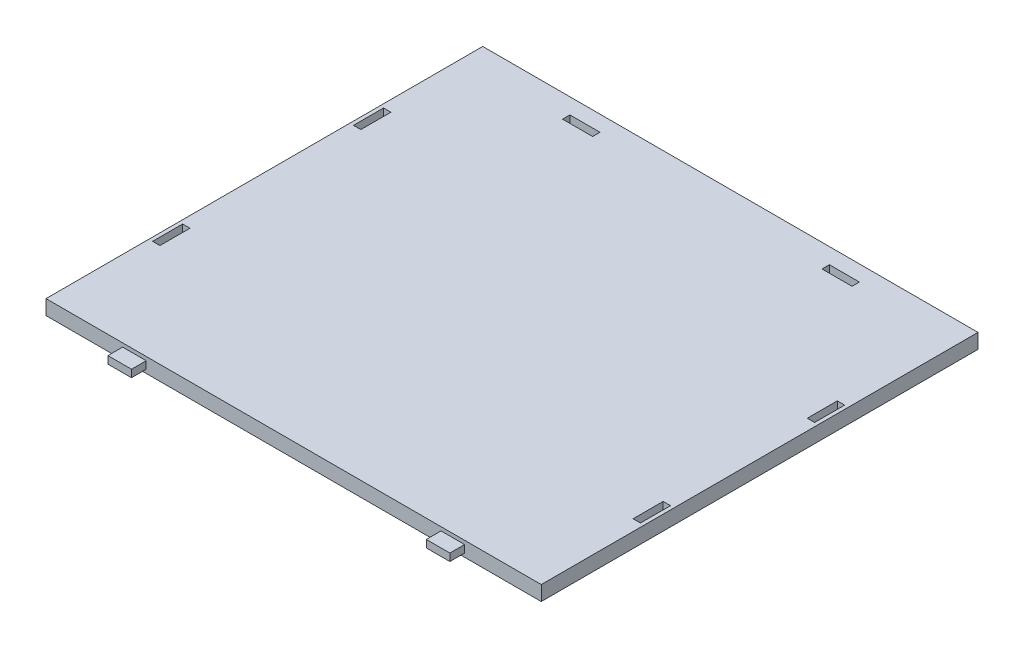
SolidWorks part; units mm, degrees
ref_plane "Alzado" through (0, 0, 0) normal (0, 0, 1) x (1, 0, 0)
ref_plane "Planta" through (0, 0, 0) normal (0, 1, 0) x (1, 0, 0)
ref_plane "Vista lateral" through (0, 0, 0) normal (1, 0, 0) x (0, 0, -1)
sketch "Croquis1" plane through (0, 0, 0) normal (0, 1, 0) x (1, 0, 0)
  line L1 (-84, 74.075) -> (84, 74.075)
  line L2 (-84, 74.075) -> (-84, -74.075)
  line L3 (-84, -74.075) -> (84, -74.075)
  line L4 (84, 74.075) -> (84, -74.075)
  line L5 (-84, 74.075) -> (84, -74.075) construction
  line L6 (-84, -74.075) -> (84, 74.075) construction
  point P0 (0, 0)
  dimension "D1" = 168
  dimension "D2" = 148.15
extrude "Saliente-Extruir1" add sketch "Croquis1" along normal blind 5
sketch "Croquis2" plane through (0, 5, 0) normal (0, 1, 0) x (1, 0, 0)
  line L0 (-79, 74.075) -> (-79, -74.075) construction
  line L1 (84, 74.075) -> (-84, 74.075) construction
  line L2 (-84, -74.075) -> (84, -74.075) construction
  line L3 (79, 74.075) -> (79, -74.075) construction
  line L4 (-84, 74.075) -> (-84, -74.075) construction
  line L5 (84, -74.075) -> (84, 74.075) construction
  line L6 (-81.5, 74.075) -> (-81.5, -74.075) construction
  line L11 (-84, 0) -> (84.3476, 0) construction
  line L12 (-84, 25) -> (84, 25) construction
  line L13 (-84, -34.075) -> (84, -34.075) construction
  line L14 (-82.75, 39.175) -> (-80.25, 39.175)
  line L15 (-82.75, 39.175) -> (-82.75, 28.975)
  line L16 (-82.75, 28.975) -> (-80.25, 28.975)
  line L17 (-80.25, 39.175) -> (-80.25, 28.975)
  line L18 (-82.75, 39.175) -> (-80.25, 28.975) construction
  line L19 (-82.75, 28.975) -> (-80.25, 39.175) construction
  line L20 (81.5, 74.075) -> (81.5, -74.075) construction
  line L21 (-82.75, -28.975) -> (-80.25, -28.975)
  line L22 (-82.75, -28.975) -> (-82.75, -39.175)
  line L23 (-82.75, -39.175) -> (-80.25, -39.175)
  line L24 (-80.25, -28.975) -> (-80.25, -39.175)
  line L25 (-82.75, -28.975) -> (-80.25, -39.175) construction
  line L26 (-82.75, -39.175) -> (-80.25, -28.975) construction
  line L28 (80.25, -28.975) -> (82.75, -28.975)
  line L29 (80.25, -28.975) -> (80.25, -39.175)
  line L30 (80.25, -39.175) -> (82.75, -39.175)
  line L31 (82.75, -28.975) -> (82.75, -39.175)
  line L32 (80.25, -28.975) -> (82.75, -39.175) construction
  line L33 (80.25, -39.175) -> (82.75, -28.975) construction
  line L34 (80.25, 30.1) -> (82.75, 30.1)
  line L35 (80.25, 30.1) -> (80.25, 19.9)
  line L36 (80.25, 19.9) -> (82.75, 19.9)
  line L37 (82.75, 30.1) -> (82.75, 19.9)
  line L38 (80.25, 30.1) -> (82.75, 19.9) construction
  line L39 (80.25, 19.9) -> (82.75, 30.1) construction
  point P12 (-80.25, 74.6701)
  point P20 (-81.5, 34.075)
  point P27 (-81.5, -34.075)
  point P34 (81.5, -34.075)
  point P39 (81.5, 25)
  dimension "D1" = 5
  dimension "D2" = 5
  dimension "D3" = 2.5
  dimension "D4" = 40
  dimension "D5" = 2.5
  dimension "D6" = 40
  dimension "D7" = 2.5
  dimension "D8" = 10.2
  dimension "D9" = 10.2
  dimension "D10" = 2.5
  dimension "D11" = 2.5
  dimension "D12" = 10.2
  dimension "D13" = 2.5
  dimension "D14" = 10.2
extrude "Cortar-Extruir1" cut sketch "Croquis2" against normal blind 5
sketch "Croquis4" plane through (0, 0, 74.075) normal (0, 0, 1) x (1, 0, 0)
  line L0 (-84, 2.5) -> (84, 2.5) construction
  line L1 (-84, 5) -> (-84, 0) construction
  line L2 (84, 5) -> (84, 0) construction
  line L4 (-58, 3.75) -> (-50, 3.75)
  line L5 (-58, 3.75) -> (-58, 1.25)
  line L6 (-58, 1.25) -> (-50, 1.25)
  line L7 (-50, 3.75) -> (-50, 1.25)
  line L8 (-58, 3.75) -> (-50, 1.25) construction
  line L9 (-58, 1.25) -> (-50, 3.75) construction
  line L10 (50, 3.75) -> (58, 3.75)
  line L11 (50, 3.75) -> (50, 1.25)
  line L12 (50, 1.25) -> (58, 1.25)
  line L13 (58, 3.75) -> (58, 1.25)
  line L14 (50, 3.75) -> (58, 1.25) construction
  line L15 (50, 1.25) -> (58, 3.75) construction
  point P6 (-54, 2.5)
  point P12 (54, 2.5)
  dimension "D1" = 2.5
  dimension "D2" = 8
  dimension "D3" = 30
  dimension "D4" = 2.5
  dimension "D5" = 8
  dimension "D6" = 30
extrude "Saliente-Extruir2" add sketch "Croquis4" along normal blind 5
sketch "Sketch1" plane through (0, 5, 0) normal (0, 1, 0) x (1, 0, 0)
  line L1 (-84, 74.075) -> (-84, 67.4989) construction
  line L2 (-84, 74.075) -> (-84, -74.075) construction
  line L3 (-84, 67.4989) -> (84, 67.4989) construction
  line L4 (84, -74.075) -> (84, 74.075) construction
  line L6 (-49.1, 68.7489) -> (-38.9, 68.7489)
  line L7 (-49.1, 68.7489) -> (-49.1, 66.2489)
  line L8 (-49.1, 66.2489) -> (-38.9, 66.2489)
  line L9 (-38.9, 68.7489) -> (-38.9, 66.2489)
  line L10 (-49.1, 68.7489) -> (-38.9, 66.2489) construction
  line L11 (-49.1, 66.2489) -> (-38.9, 68.7489) construction
  line L12 (38.9, 68.7489) -> (49.1, 68.7489)
  line L13 (38.9, 68.7489) -> (38.9, 66.2489)
  line L14 (38.9, 66.2489) -> (49.1, 66.2489)
  line L15 (49.1, 68.7489) -> (49.1, 66.2489)
  line L16 (38.9, 68.7489) -> (49.1, 66.2489) construction
  line L17 (38.9, 66.2489) -> (49.1, 68.7489) construction
  point P0 (-44, 67.4989)
  point P13 (44, 67.4989)
  dimension "D1" = 6.5761
  dimension "D2" = 10.2
  dimension "D3" = 2.5
  dimension "D4" = 10.2
  dimension "D5" = 2.5
  dimension "D6" = 40
  dimension "D7" = 40
extrude "Cut-Extrude2" cut sketch "Sketch1" against normal blind 5
